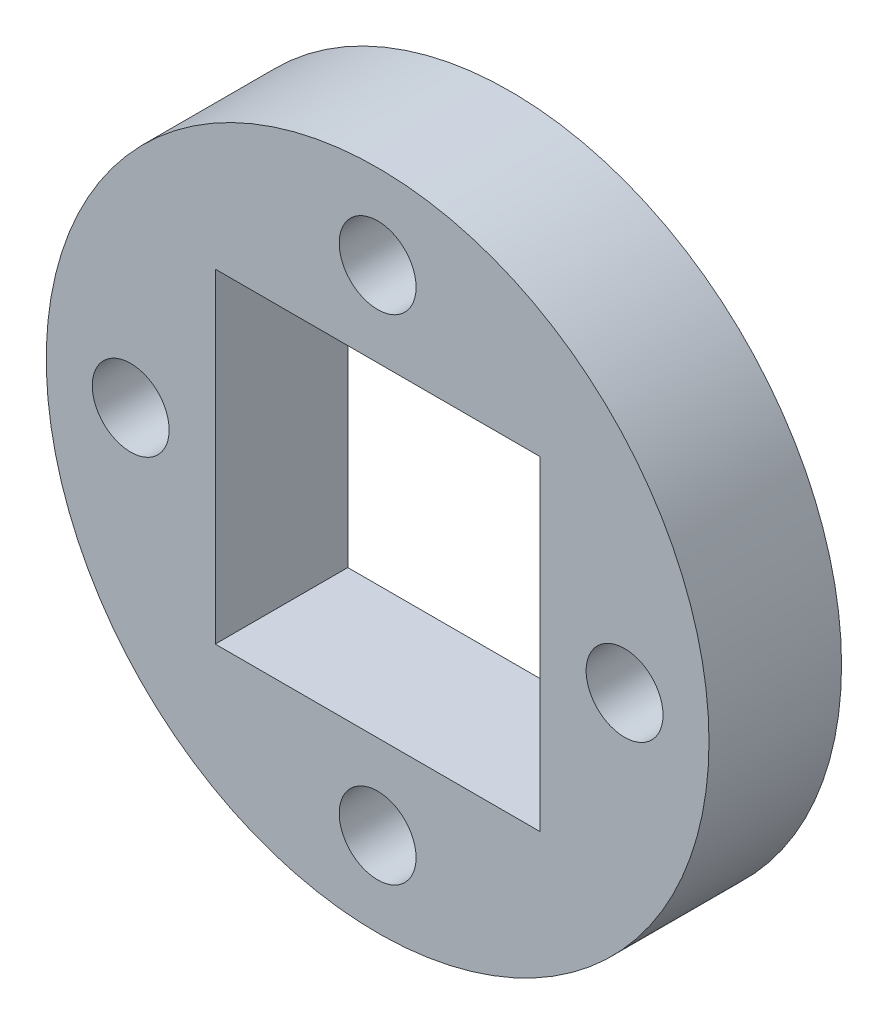
SolidWorks part; units mm, degrees
ref_plane "Front Plane" through (0, 0, 0) normal (0, 0, 1) x (1, 0, 0)
ref_plane "Top Plane" through (0, 0, 0) normal (0, 1, 0) x (1, 0, 0)
ref_plane "Right Plane" through (0, 0, 0) normal (1, 0, 0) x (0, 0, -1)
sketch "Sketch1" plane through (0, 0, 0) normal (0, 0, 1) x (1, 0, 0)
  circle A0 centre (0, 0) radius 12.5
  dimension "D2" = 25
extrude "Boss-Extrude1" add sketch "Sketch1" along normal mid plane 5
sketch "Sketch8" plane through (0, 0, 2.5) normal (0, 0, 1) x (1, 0, 0)
  line L2 (-6.125, 6.125) -> (6.125, 6.125)
  line L3 (-6.125, 6.125) -> (-6.125, -6.125)
  line L4 (-6.125, -6.125) -> (6.125, -6.125)
  line L5 (6.125, 6.125) -> (6.125, -6.125)
  line L6 (-6.125, 6.125) -> (6.125, -6.125) construction
  line L7 (-6.125, -6.125) -> (6.125, 6.125) construction
  point P5 (0, 0)
  point P14 (0, 0)
  dimension "D1" = 12.25
extrude "Cut-Extrude1" cut sketch "Sketch8" against normal up to next
sketch "Sketch11" plane through (0, 0, 2.5) normal (0, 0, 1) x (1, 0, 0)
  line L0 (6.125, -6.125) -> (6.125, 6.125) construction
  circle A0 centre (9.315, 0) radius 1.45
  circle A1 centre (0, -9.315) radius 1.45
  circle A2 centre (-9.315, 0) radius 1.45
  circle A3 centre (0, 9.315) radius 1.45
  point P13 (0, 0)
  dimension "D1" = 2.9
  dimension "D2" = 3.19
  dimension "D3" = 4
extrude "Cut-Extrude4" cut sketch "Sketch11" against normal up to next
equation "\"drumDiameter\"= 25"
equation "\"drumLength\"=5"
equation "\"foamThickness\"= 5"
equation "\"drumAbove\"= 0.6"
equation "\"holderThicc\"= 2"
equation "\"D1@Boss-Extrude1\"=\"drumLength\""
equation "\"squareBarLength\"= 12.25"
equation "\"D1@Sketch8\"=\"squareBarLength\""
equation "\"toothlen\"= 2.5"
